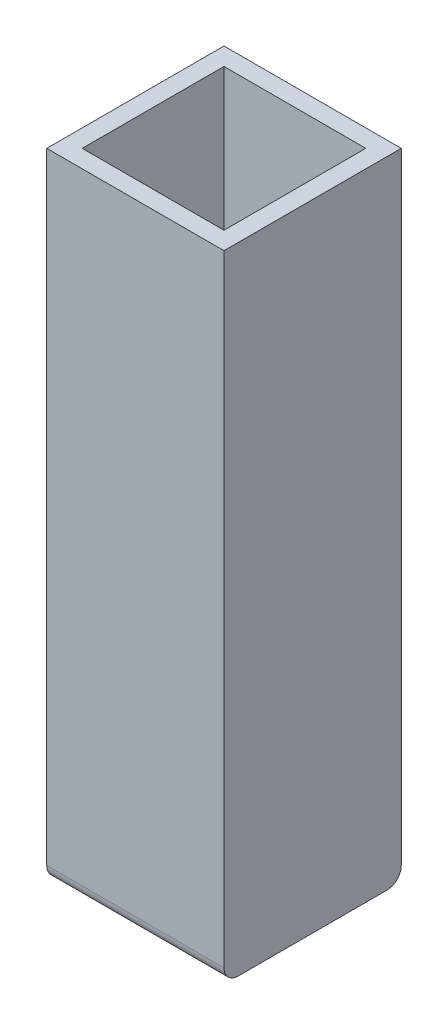
SolidWorks part; units mm, degrees
material "ПВХ Жесткий"
ref_plane "Спереди" through (0, 0, 0) normal (0, 0, 1) x (1, 0, 0)
ref_plane "Сверху" through (0, 0, 0) normal (0, 1, 0) x (1, 0, 0)
ref_plane "Справа" through (0, 0, 0) normal (1, 0, 0) x (0, 0, -1)
sketch "Эскиз1" plane through (0, 0, 0) normal (0, 1, 0) x (1, 0, 0)
  line L0 (0, 0) -> (12.5, 0)
  line L1 (0, 0) -> (0, 12.5)
  line L2 (12.5, 0) -> (12.5, 12.5)
  line L3 (0, 12.5) -> (12.5, 12.5)
  dimension "D1" = 12.5
extrude "Бобышка-Вытянуть1" add sketch "Эскиз1" along normal blind 44.8
sketch "Эскиз2" plane through (0, 44.8, 0) normal (0, 1, 0) x (1, 0, 0)
  line L0 (6.25, 12.5) -> (6.25, 0) construction
  line L1 (12.5, 12.5) -> (0, 12.5) construction
  line L2 (0, 0) -> (12.5, 0) construction
  line L3 (0, 6.25) -> (12.5, 6.25) construction
  line L4 (0, 12.5) -> (0, 0) construction
  line L5 (12.5, 0) -> (12.5, 12.5) construction
  line L6 (1.25, 11.25) -> (11.25, 11.25)
  line L7 (1.25, 11.25) -> (1.25, 1.25)
  line L8 (11.25, 11.25) -> (11.25, 1.25)
  line L9 (1.25, 1.25) -> (11.25, 1.25)
  point P12 (6.25, 11.25)
  point P15 (11.25, 6.25)
  dimension "D1" = 10
extrude "Вырез-Вытянуть1" cut sketch "Эскиз2" against normal blind 44
fillet "Скругление1" radius 1 2 edges at (6.25, 0, 0) (6.25, 0, -12.5)
sketch "Эскиз3" plane through (0, 44.8, 0) normal (0, 1, 0) x (1, 0, 0)
  line L0 (6.25, 12.5) -> (6.25, 0) construction
  line L1 (12.5, 12.5) -> (0, 12.5) construction
  line L2 (0, 0) -> (12.5, 0) construction
  line L3 (12.5, 6.25) -> (0, 6.25) construction
  line L4 (12.5, 0) -> (12.5, 12.5) construction
  line L5 (0, 12.5) -> (0, 0) construction
